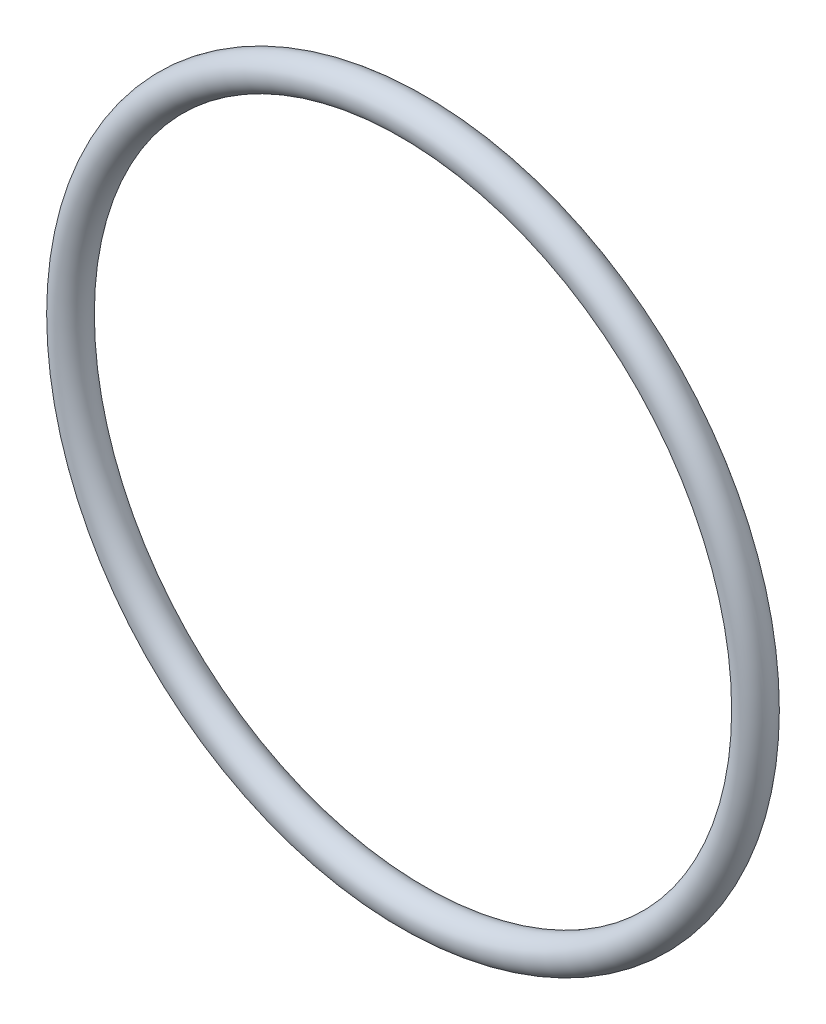
SolidWorks part; units mm, degrees
ref_plane "Front" through (0, 0, 0) normal (0, 0, 1) x (1, 0, 0)
ref_plane "Top" through (0, 0, 0) normal (0, 1, 0) x (1, 0, 0)
ref_plane "Right" through (0, 0, 0) normal (1, 0, 0) x (0, 0, -1)
sketch "Sketch1" plane through (0, 0, 0) normal (1, 0, 0) x (0, -1, 0)
  line L0 (0, -1.3081) -> (0, 1.3081) construction
  line L2 (-30.6362, 0) -> (30.6362, 0) construction
  line L3 (-25.2349, 0) -> (25.2349, 0) construction
  circle A0 centre (26.543, 0) radius 1.3081
  point P9 (25.2349, 0)
  point P10 (27.8511, 0)
  point P13 (26.543, 1.3081)
  point P14 (26.543, -1.3081)
  dimension "Width" = 2.6162
  dimension "ID" = 50.4698
revolve "Revolve1" add sketch "Sketch1" angle 360 about L0
